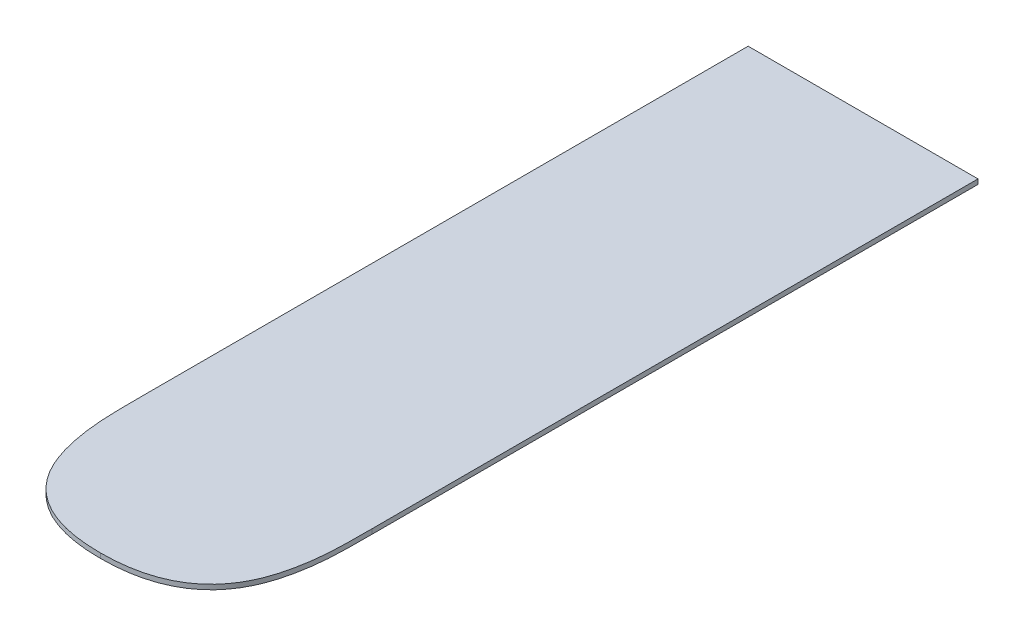
SolidWorks part; units mm, degrees
ref_plane "Front" through (0, 0, 0) normal (0, 0, 1) x (1, 0, 0)
ref_plane "Top" through (0, 0, 0) normal (0, 1, 0) x (1, 0, 0)
ref_plane "Right" through (0, 0, 0) normal (1, 0, 0) x (0, 0, -1)
sketch "Sketch2" plane through (0, 0, 0) normal (0, 1, 0) x (1, 0, 0)
  line L0 (139.7, -1270) -> (139.7, 63.5)
  line L8 (0, -1460.5) -> (441.3665, -1460.5) construction
  line L9 (0, 381) -> (319.7263, 381) construction
  spline S0 degree 3 poles (0, -1460.5) (108.685, -1460.5) (137.2012, -1361.3853) (139.7, -1312.0378) (139.7, -1270) knots 0 0 0 0 0.140311 0.20061 0.20061 0.20061 0.20061
  spline S2 degree 3 poles (139.7, 63.5) (139.7, 105.4099) (138.7759, 206.4957) (73.5078, 381) (0, 381) knots 0.803818 0.803818 0.803818 0.803818 0.866735 1 1 1 1
  point P36 (70.6307, -1446.9472)
sketch "Sketch3" plane through (0, 0, 0) normal (0, 1, 0) x (1, 0, 0)
  line L0 (0, 381) -> (0, -1460.5)
  line L1 (139.7, -1270) -> (139.7, 63.5) construction
  line L2 (139.7, -1270) -> (139.7, 63.5)
  spline S0 degree 3 poles (1025.6675, -3831.9969) (-39.0223, -26.9755) (418.1083, -122.1769) (-293.9095, 1116.6594) (-981.356, -3470.7577) knots 0.474027 0.474027 0.474027 0.474027 0.866735 1.310287 1.310287 1.310287 1.310287 only from (139.7, 63.5) to (0, 381) construction
  spline S1 degree 3 poles (-3210.7154, 892.7422) (-54.9132, -1919.6755) (220.175, -1221.285) (106.9015, -1265.7705) (210.1254, 2729.0414) knots -0.329125 -0.329125 -0.329125 -0.329125 0.140311 0.445941 0.445941 0.445941 0.445941 only from (0, -1460.5) to (139.7, -1270) construction
  spline S2 degree 3 poles (139.7, 63.5) (139.7, 105.4099) (138.7759, 206.4957) (73.5078, 381) (0, 381) knots 0.803818 0.803818 0.803818 0.803818 0.866735 1 1 1 1
  spline S3 degree 3 poles (0, -1460.5) (108.685, -1460.5) (137.2012, -1361.3853) (139.7, -1312.0378) (139.7, -1270) knots 0 0 0 0 0.140311 0.20061 0.20061 0.20061 0.20061
extrude "Boss-Extrude1" add sketch "Sketch3" along normal blind 5.842
sketch "Sketch4" plane through (0, 0, 0) normal (0, 1, 0) x (1, 0, 0)
  line L0 (139.7, -1270) -> (139.7, 63.5) construction
  line L1 (0, 381) -> (139.7, 381)
  line L2 (0, 381) -> (0, -533.4)
  line L3 (0, -533.4) -> (139.7, -533.4)
  line L4 (139.7, 381) -> (139.7, -533.4)
  dimension "D1" = 914.4
extrude "Cut-Extrude1" cut sketch "Sketch4" along normal through all
mirror "Mirror1" about plane through (0, 0, 0) normal (1, 0, 0) of bodies 103 101
